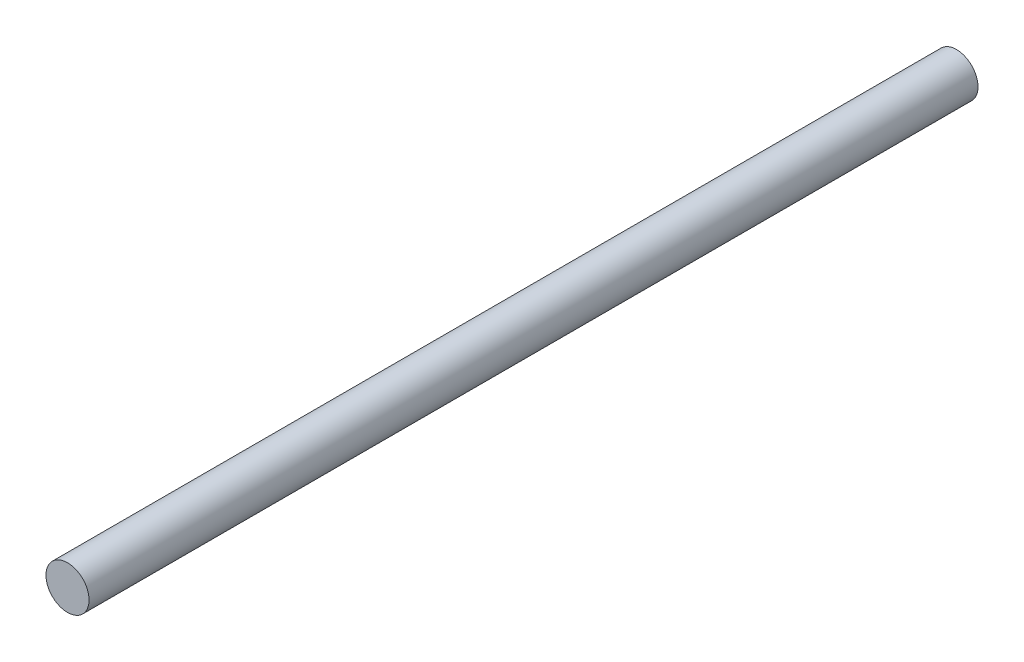
SolidWorks part; units mm, degrees
ref_plane "Front Plane" through (0, 0, 0) normal (0, 0, 1) x (1, 0, 0)
ref_plane "Top Plane" through (0, 0, 0) normal (0, 1, 0) x (1, 0, 0)
ref_plane "Right Plane" through (0, 0, 0) normal (1, 0, 0) x (0, 0, -1)
sketch "Sketch1" plane through (0, 0, 0) normal (0, 0, 1) x (1, 0, 0)
  circle A0 centre (0, 0) radius 1.016
  dimension "D1" = 2.032
extrude "Boss-Extrude1" add sketch "Sketch1" along normal blind 41.91
ref_plane "Plane1" through (0, 0, 41.91) normal (0, 0, 1) x (1, 0, 0)
ref_plane "Plane2" through (0, 0, 0) normal (0, 0, -1) x (-1, 0, 0)
sketch "Sketch2" plane through (0, 0, 0) normal (0, 0, -1) x (-1, 0, 0)
  circle A0 centre (0, 0) radius 2.4892
  dimension "D1" = 4.9784
sketch "Sketch5" plane through (0, 0, 41.91) normal (0, 0, 1) x (1, 0, 0)
  circle A0 centre (0, 0) radius 2.4892
  dimension "D1" = 4.9784
